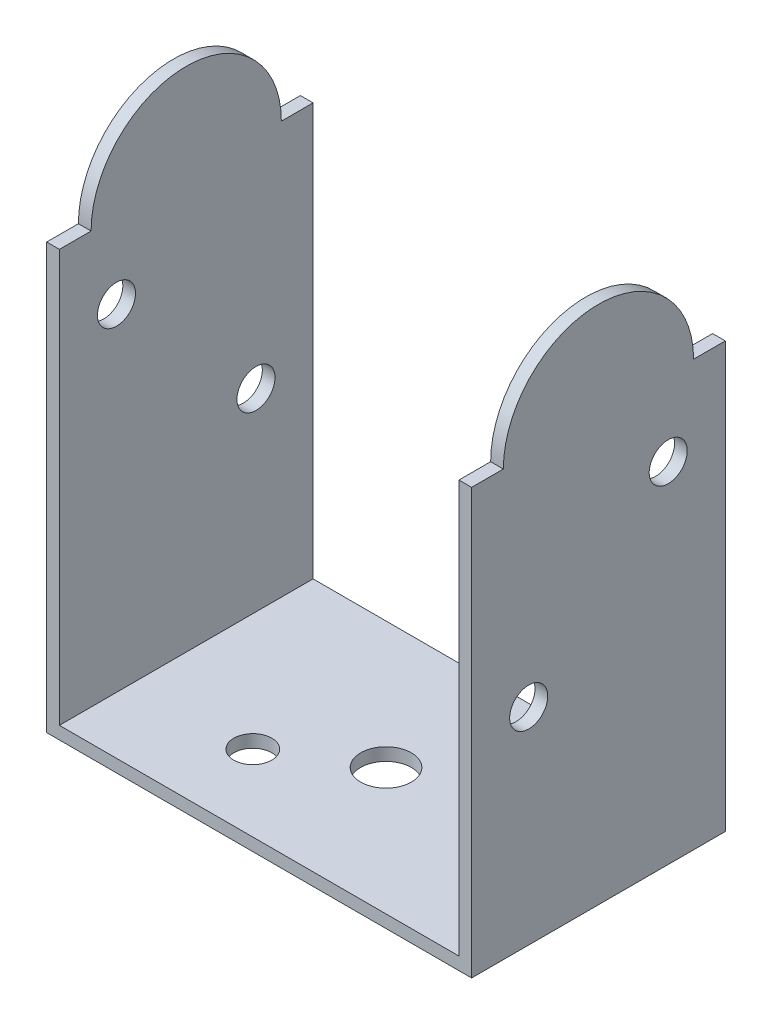
SolidWorks part; units mm, degrees
ref_plane "Front Plane" through (0, 0, 0) normal (0, 0, 1) x (1, 0, 0)
ref_plane "Top Plane" through (0, 0, 0) normal (0, 1, 0) x (1, 0, 0)
ref_plane "Right Plane" through (0, 0, 0) normal (1, 0, 0) x (0, 0, -1)
sketch "MetalPart" plane through (0, 0, 0) normal (0, 0, 1) x (1, 0, 0)
  line L0 (0, 0) -> (-33.5, 0)
  line L1 (-33.5, 0) -> (-33.5, 82)
  line L2 (-33.5, 82) -> (-31.5, 82)
  line L3 (-31.5, 82) -> (-31.5, 2)
  line L4 (-31.5, 2) -> (31.5, 2)
  line L5 (31.5, 2) -> (31.5, 82)
  line L6 (31.5, 82) -> (33.5, 82)
  line L7 (33.5, 82) -> (33.5, 0)
  line L8 (33.5, 0) -> (0, 0)
  line L9 (0, 79.526) -> (0, -76.5291) construction
  dimension "D1" = 33.5
  dimension "D2" = 33.5
  dimension "D3" = 82
  dimension "D4" = 82
  dimension "D5" = 2
  dimension "D6" = 2
  dimension "D7" = 2
extrude "Boss-Extrude1" add sketch "MetalPart" along normal blind 40
sketch "Sketch2" plane through (0, 0, 0) normal (0, -1, 0) x (1, 0, 0)
  line L0 (0, 63.8702) -> (0, -26.616) construction
  line L1 (-74.4483, 20) -> (74.4483, 20) construction
  line L2 (-33.5, 40) -> (33.5, 40) construction
  line L4 (-33.5, 40) -> (-33.5, 0) construction
  circle A0 centre (0, 20) radius 4
  circle A1 centre (-13, 28) radius 3
  circle A2 centre (13, 12) radius 3
  point P5 (0, 20)
  dimension "D3" = 6
  dimension "D4" = 6
  dimension "D9" = 8
  dimension "D1" = 20
  dimension "D2" = 33.5
  dimension "D5" = 8
  dimension "D6" = 13
  dimension "D7" = 8
  dimension "D8" = 13
extrude "Cut-Extrude2" cut sketch "Sketch2" against normal blind 2 contours A2 | A0 | A1
sketch "Sketch3" plane through (33.5, 0, 0) normal (1, 0, 0) x (0, 0, -1)
  line L0 (-20, 112.2825) -> (-20, 82) construction
  line L1 (-40, 67) -> (-35, 67)
  line L2 (-40, 0) -> (-40, 82) construction
  line L3 (0, 67) -> (-5, 67)
  line L4 (0, 0) -> (0, 82) construction
  line L5 (-20, 52) -> (-20, -29.8081) construction
  arc A0 (-5, 67) -> (-35, 67) centre (-20, 67) ccw
  dimension "D1" = 5
  dimension "D2" = 5
  dimension "D3" = 15
extrude "Cut-Extrude8" cut sketch "Sketch3" against normal blind 2 and the other way through all flip side to cut
sketch "Sketch5" plane through (33.5, 0, 0) normal (1, 0, 0) x (0, 0, -1)
  line L0 (-20, -22.705) -> (-20, 102.7119) construction
  line L1 (-40, 0) -> (0, 0) construction
  circle A0 centre (-9, 55) radius 3
  circle A1 centre (-31, 32.5) radius 3
  dimension "D1" = 55
  dimension "D2" = 32.5
  dimension "D3" = 11
  dimension "D4" = 11
extrude "Cut-Extrude9" cut sketch "Sketch5" against normal blind 2
sketch "Sketch6" plane through (-33.5, 0, 0) normal (-1, 0, 0) x (0, 0, 1)
  line L0 (20, 106.7938) -> (20, -14.2837) construction
  line L1 (40, 0) -> (0, 0) construction
  circle A0 centre (9, 32.5) radius 3
  circle A1 centre (31, 55) radius 3
  dimension "D1" = 11
  dimension "D5" = 6
  dimension "D6" = 6
  dimension "D2" = 11
  dimension "D3" = 55
  dimension "D4" = 32.5
extrude "Cut-Extrude10" cut sketch "Sketch6" against normal blind 2
sketch "Sketch7" plane through (-33.5, 0, 0) normal (-1, 0, 0) x (0, 0, 1)
  line L0 (20, -18.3035) -> (20, 52) construction
  line L1 (0, 67) -> (5, 67)
  line L2 (0, 82) -> (0, 0) construction
  line L3 (40, 67) -> (35, 67)
  line L4 (40, 82) -> (40, 0) construction
  line L5 (20, 82) -> (20, 120.3767) construction
  arc A0 (35, 67) -> (5, 67) centre (20, 67) ccw
  dimension "D1" = 5
  dimension "D2" = 5
  dimension "D3" = 15
extrude "Cut-Extrude11" cut sketch "Sketch7" against normal blind 2 and the other way through all flip side to cut
